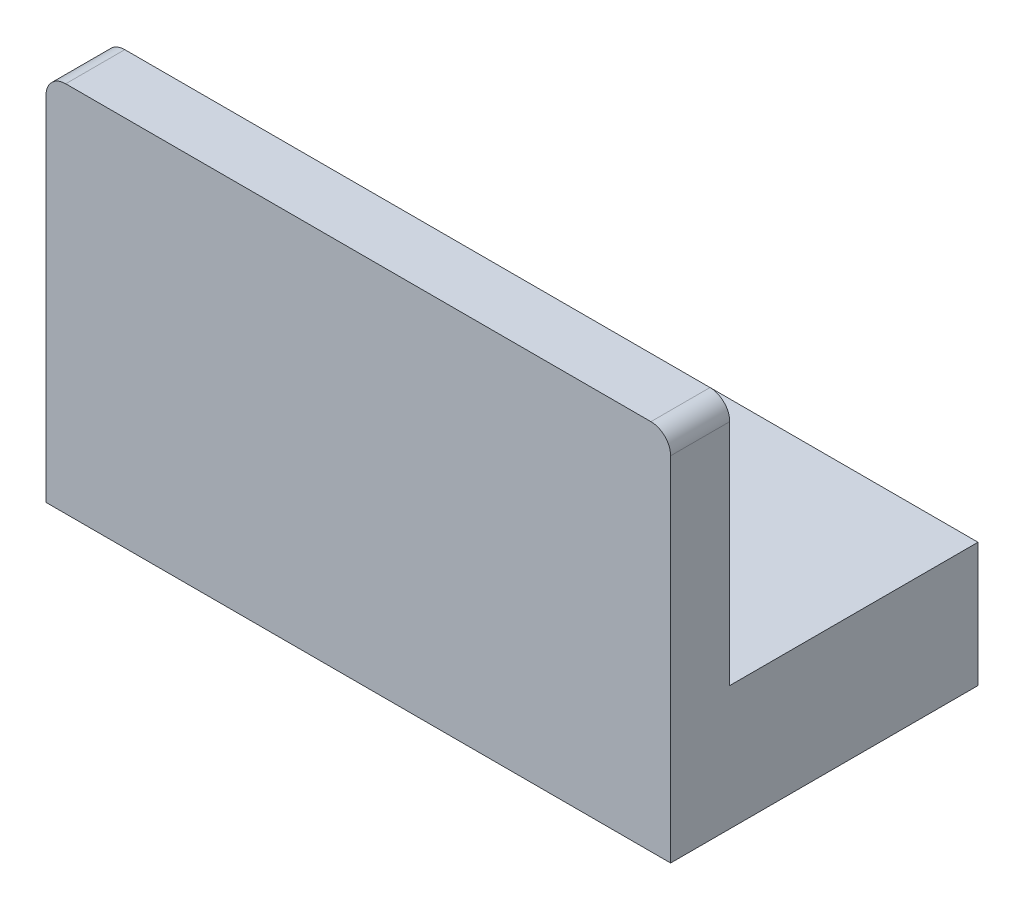
SolidWorks part; units mm, degrees
ref_plane "Front Plane" through (0, 0, 0) normal (0, 0, 1) x (1, 0, 0)
ref_plane "Top Plane" through (0, 0, 0) normal (0, 1, 0) x (1, 0, 0)
ref_plane "Right Plane" through (0, 0, 0) normal (1, 0, 0) x (0, 0, -1)
sketch "Sketch1" plane through (0, 0, 0) normal (1, 0, 0) x (0, 0, -1)
  line L0 (0, 0) -> (7.8, 0)
  line L1 (7.8, 0) -> (7.8, 3.15)
  line L2 (7.8, 3.15) -> (1.5, 3.15)
  line L3 (1.5, 3.15) -> (1.5, 9.45)
  line L4 (1.5, 9.45) -> (0, 9.45)
  line L5 (0, 9.45) -> (0, 0)
  point P4 (0.75, 9.45)
  dimension "D1" = 7.8
  dimension "D2" = 3.15
  dimension "D3" = 1.5
  dimension "D4" = 6.3
extrude "Boss-Extrude1" add sketch "Sketch1" against normal blind 15.85
shell "Shell1" thickness 1.55
sketch "Sketch2" plane through (0, 1.6, 0) normal (0, -1, 0) x (1, 0, 0)
  line L1 (-15.85, 0) -> (-15.85, -7.8) construction
  line L2 (-15.85, -7.8) -> (0, -7.8) construction
  circle A0 centre (-7.925, -3.9) radius 1.5
  circle A1 centre (-7.925, -3.9) radius 0.7
  dimension "D3" = 3
  dimension "D4" = 1.4
  dimension "D1" = 7.925
  dimension "D2" = 3.9
extrude "Boss-Extrude2" add sketch "Sketch2" along normal offset from surface (1.4 mm away) 0.2 up to face at (-7.925, 0, -3.9)
fillet "Fillet1" radius 0.5 2 edges at (0, 9.45, -0.75) (-15.85, 9.45, -0.75)
